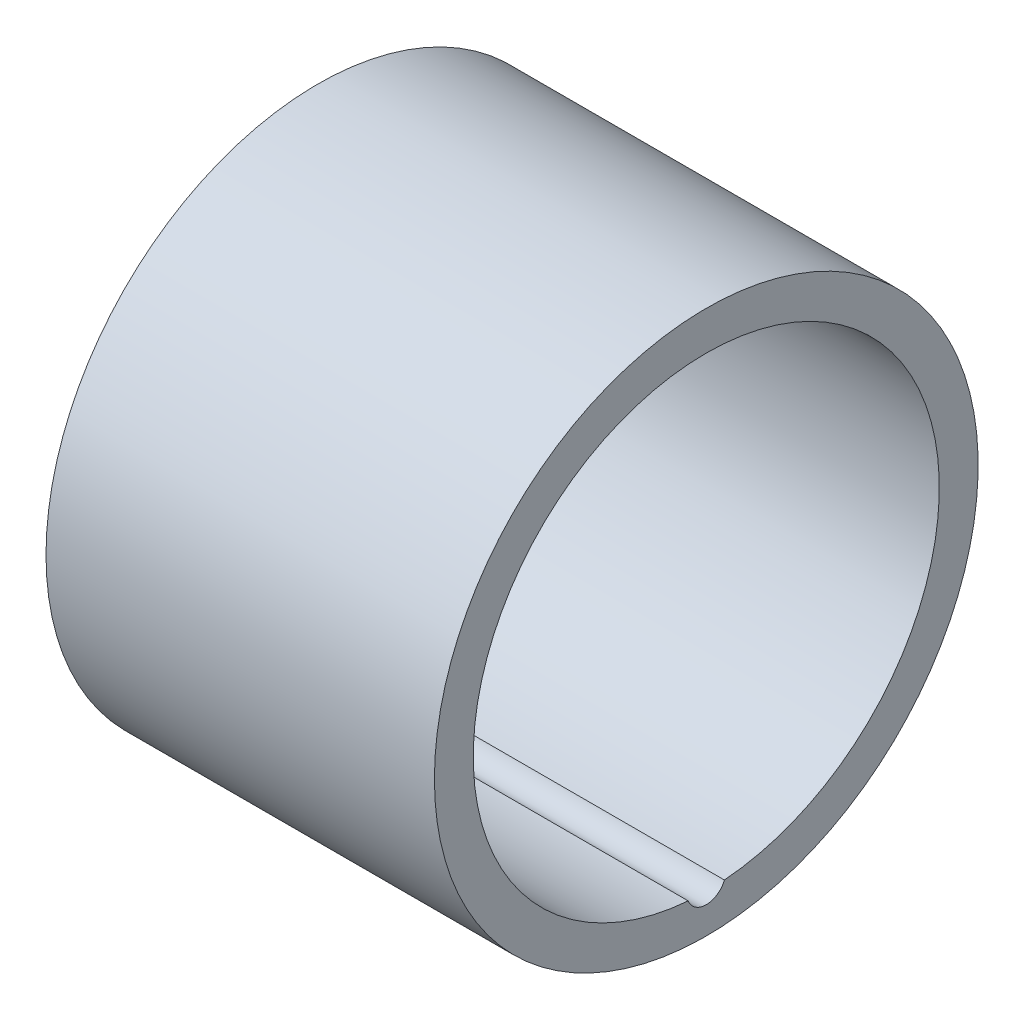
SolidWorks part; units mm, degrees
ref_plane "Plan1" through (0, 0, 0) normal (0, 0, 1) x (1, 0, 0)
ref_plane "Plan2" through (0, 0, 0) normal (0, 1, 0) x (1, 0, 0)
ref_plane "Plan3" through (0, 0, 0) normal (1, 0, 0) x (0, 0, -1)
sketch "Esquisse1" plane through (0, 0, 0) normal (0, 0, 1) x (1, 0, 0)
  line L0 (0, 0) -> (40, 0) construction
  line L1 (0, 6) -> (10, 6)
  dimension "D1" = 10
  dimension "D2" = 6
revolve "Base-Révol.-Mince" add sketch "Esquisse1" angle 360 about L0
sketch "Esquisse2" plane through (0, 0, 0) normal (1, 0, 0) x (0, 0, -1)
  line L0 (-10, -6) -> (10, -6) construction
  line L1 (0, -6.3) -> (10, -6.3) construction
  circle A0 centre (0, 0) radius 6 construction
  circle A1 centre (0, -5.8) radius 0.5
  point P4 (0, -6)
  dimension "D2" = 1
  dimension "D1" = 0.3
extrude "Enlèv. mat.-Extru.2" cut sketch "Esquisse2" along normal through all
